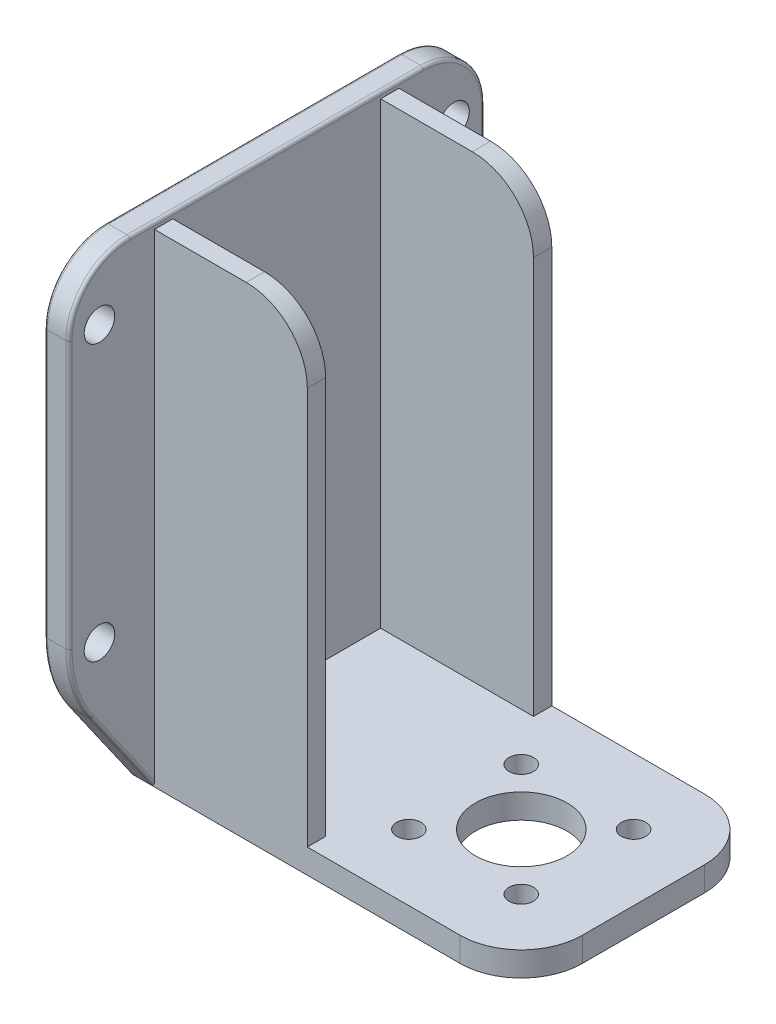
SolidWorks part; units mm, degrees
ref_plane "前视基准面" through (0, 0, 0) normal (0, 0, 1) x (1, 0, 0)
ref_plane "上视基准面" through (0, 0, 0) normal (0, 1, 0) x (1, 0, 0)
ref_plane "右视基准面" through (0, 0, 0) normal (1, 0, 0) x (0, 0, -1)
sketch "草图1" plane through (0, 0, 0) normal (0, 1, 0) x (1, 0, 0)
  line L0 (-53.6296, 39.7094) -> (-53.6296, -0.2906) construction
  line L1 (-73.6296, 39.7094) -> (-13.6296, 39.7094)
  line L2 (-73.6296, 39.7094) -> (-73.6296, -0.2906)
  line L3 (-73.6296, -0.2906) -> (-13.6296, -0.2906)
  line L4 (-13.6296, 39.7094) -> (-13.6296, -0.2906)
  circle A0 centre (-33.6296, 19.7094) radius 7.5
  circle A1 centre (-42.822, 28.9018) radius 2
  circle A2 centre (-24.4372, 28.9018) radius 2
  circle A3 centre (-24.4372, 10.517) radius 2
  circle A4 centre (-42.822, 10.517) radius 2
  point P18 (-33.6296, 19.7094)
  dimension "D2" = 15
  dimension "D3" = 4
  dimension "D1" = 60
  dimension "D4" = 13
  dimension "D6" = 40
  dimension "D7" = 40
  dimension "D5" = 4
extrude "凸台-拉伸1" add sketch "草图1" along normal blind 4
sketch "草图2" plane through (-73.6296, 0, 0) normal (-1, 0, 0) x (0, 0, 1)
  line L0 (-53.7135, 20) -> (-39.7094, 0)
  line L1 (-53.7135, 20) -> (14.2948, 20)
  line L2 (-39.7094, 0) -> (0.2906, 0)
  line L3 (14.2948, 20) -> (0.2906, 0)
  line L4 (-39.7094, 0) -> (0.2906, 0) construction
  dimension "D1" = 20
  dimension "D2" = 55
  dimension "D3" = 55
  dimension "D4" = 68.0083
extrude "凸台-拉伸2" add sketch "草图2" along normal blind 4
sketch "草图6" plane through (0, 20, 0) normal (0, 1, 0) x (1, 0, 0)
  line L1 (-73.6296, 53.7135) -> (-77.6296, 53.7135)
  line L2 (-73.6296, 53.7135) -> (-73.6296, -14.2948)
  line L3 (-73.6296, -14.2948) -> (-77.6296, -14.2948)
  line L4 (-77.6296, 53.7135) -> (-77.6296, -14.2948)
extrude "凸台-拉伸3" add sketch "草图6" along normal blind 60
sketch "草图7" plane through (-73.6296, 0, 0) normal (1, 0, 0) x (0, 0, -1)
  line L0 (53.7135, 80) -> (53.7135, 20) construction
  line L1 (-14.2948, 80) -> (-14.2948, 20) construction
  line L2 (-14.2948, 80) -> (53.7135, 80) construction
  circle A0 centre (48.7135, 25) radius 2.5
  circle A1 centre (-9.2865, 25) radius 2.5
  circle A2 centre (48.7135, 70) radius 2.5
  circle A3 centre (-9.2865, 70) radius 2.5
  dimension "D1" = 5
  dimension "D3" = 58
  dimension "D4" = 5
  dimension "D5" = 5.0083
  dimension "D6" = 45
  dimension "D7" = 10
extrude "切除-拉伸1" cut sketch "草图7" against normal through all
fillet "圆角1" radius 10 2 edges at (-13.6296, 2, 0.2906) (-13.6296, 2, -39.7094)
fillet "圆角2" radius 20 2 edges at (-75.6296, 20, -53.7135) (-75.6296, 20, 14.2948)
fillet "圆角4" radius 10 2 edges at (-75.6296, 80, 14.2948) (-75.6296, 80, -53.7135)
sketch "草图8" plane through (0, 0, -39.7094) normal (0, 0, -1) x (-1, 0, 0)
  line L0 (73.6296, 4) -> (63.6296, 4)
  line L1 (23.6296, 4) -> (73.6296, 4) construction
  line L2 (63.6296, 4) -> (73.6296, 14)
  line L3 (73.6296, 14) -> (73.6296, 4)
  dimension "D1" = 10
  dimension "D2" = 10
extrude "凸台-拉伸4" [suppressed] add sketch "草图8" against normal blind 3
sketch "草图9" plane through (0, 0, 0.2906) normal (0, 0, 1) x (1, 0, 0)
  line L0 (-73.6296, 4) -> (-63.6296, 4)
  line L1 (-73.6296, 4) -> (-23.6296, 4) construction
  line L2 (-63.6296, 4) -> (-73.6296, 14)
  line L3 (-73.6296, 14) -> (-73.6296, 4)
  dimension "D1" = 10
  dimension "D2" = 10
extrude "凸台-拉伸5" [suppressed] add sketch "草图9" against normal blind 3
fillet "圆角5" [suppressed] radius 0.5
fillet "圆角12" radius 0.5 9 edges at (-73.6296, 7.4172, -44.903) (-73.6296, 20.2919, -52.7879) (-73.6296, 48.153, -53.7135) (-73.6296, 77.0711, -50.7846) (-73.6296, 80, -19.7094) (-73.6296, 77.0711, 11.3659) (-73.6296, 7.4172, 5.4842) (-73.6296, 20.2919, 13.3691) (-73.6296, 48.153, 14.2948)
fillet "圆角13" radius 0.5 9 edges at (-77.6296, 7.4172, -44.903) (-77.6296, 20.2919, -52.7879) (-77.6296, 48.153, -53.7135) (-77.6296, 77.0711, -50.7846) (-77.6296, 80, -19.7094) (-77.6296, 77.0711, 11.3659) (-77.6296, 7.4172, 5.4842) (-77.6296, 20.2919, 13.3691) (-77.6296, 48.153, 14.2948)
fillet "圆角14" [suppressed] radius 0.5
fillet "圆角15" [suppressed] radius 0.5
sketch "草图10" plane through (0, 4, 0) normal (0, 1, 0) x (1, 0, 0)
  line L1 (-73.6296, 39.7094) -> (-48.6296, 39.7094)
  line L2 (-73.6296, 39.7094) -> (-73.6296, 36.7094)
  line L3 (-73.6296, 36.7094) -> (-48.6296, 36.7094)
  line L4 (-48.6296, 39.7094) -> (-48.6296, 36.7094)
  line L5 (-73.6296, -0.2906) -> (-48.6296, -0.2906)
  line L6 (-73.6296, -0.2906) -> (-73.6296, 2.7094)
  line L7 (-73.6296, 2.7094) -> (-48.6296, 2.7094)
  line L8 (-48.6296, -0.2906) -> (-48.6296, 2.7094)
  dimension "D1" = 25
  dimension "D2" = 3
extrude "凸台-拉伸6" add sketch "草图10" along normal blind 75
fillet "圆角16" radius 10 2 edges at (-48.6296, 79, -1.2094) (-48.6296, 79, -38.2094)
